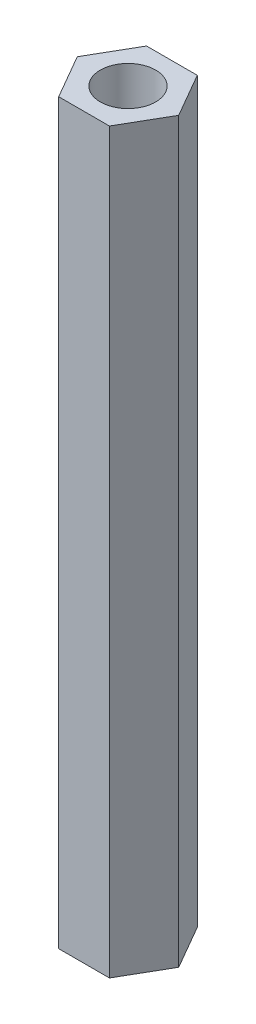
SolidWorks part; units mm, degrees
material "Brass"
ref_plane "Front Plane" through (0, 0, 0) normal (0, 0, 1) x (1, 0, 0)
ref_plane "Top Plane" through (0, 0, 0) normal (0, 1, 0) x (1, 0, 0)
ref_plane "Right Plane" through (0, 0, 0) normal (1, 0, 0) x (0, 0, -1)
sketch "Sketch1" plane through (0, 0, 0) normal (0, 1, 0) x (1, 0, 0)
  line L1 (2.75, 0) -> (1.375, 2.3816)
  line L2 (1.375, 2.3816) -> (-1.375, 2.3816)
  line L3 (-1.375, 2.3816) -> (-2.75, 0)
  line L4 (-2.75, 0) -> (-1.375, -2.3816)
  line L5 (-1.375, -2.3816) -> (1.375, -2.3816)
  line L6 (1.375, -2.3816) -> (2.75, 0)
  circle A1 centre (0, 0) radius 2.3816 construction
  circle A2 centre (0, 0) radius 1.5
  dimension "D1" = 3
extrude "Boss-Extrude1" add sketch "Sketch1" along normal blind 40
